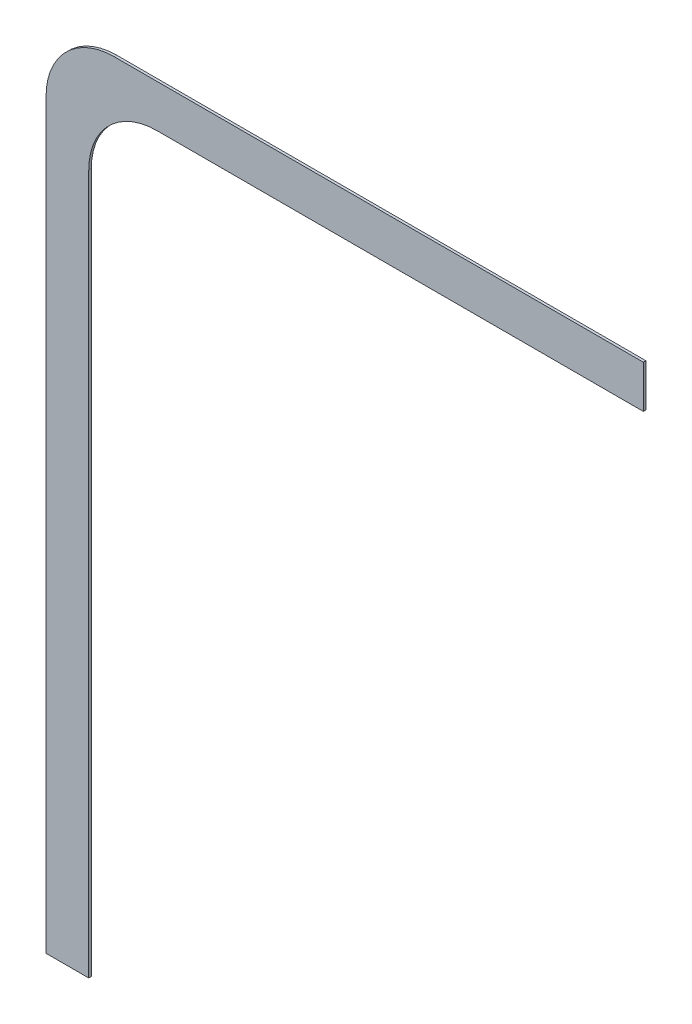
SolidWorks part; units mm, degrees
ref_plane "Front Plane" through (0, 0, 0) normal (0, 0, 1) x (1, 0, 0)
ref_plane "Top Plane" through (0, 0, 0) normal (0, 1, 0) x (1, 0, 0)
ref_plane "Right Plane" through (0, 0, 0) normal (1, 0, 0) x (0, 0, -1)
sketch "Sketch1" plane through (0, 0, 0) normal (0, 0, 1) x (1, 0, 0)
  line L0 (0, 0) -> (0, 870)
  line L1 (80, 950) -> (700, 950)
  line L2 (700, 950) -> (700, 900)
  line L3 (700, 900) -> (130, 900)
  line L4 (50, 820) -> (50, 0)
  line L5 (50, 0) -> (0, 0)
  arc A0 (130, 900) -> (50, 820) centre (130, 820) ccw
  arc A1 (0, 870) -> (80, 950) centre (80, 870) cw
  point P11 (0, 950)
  dimension "D4" = 900
  dimension "D1" = 570
  dimension "D2" = 700
  dimension "D3" = 50
extrude "Boss-Extrude1" add sketch "Sketch1" along normal blind 3
